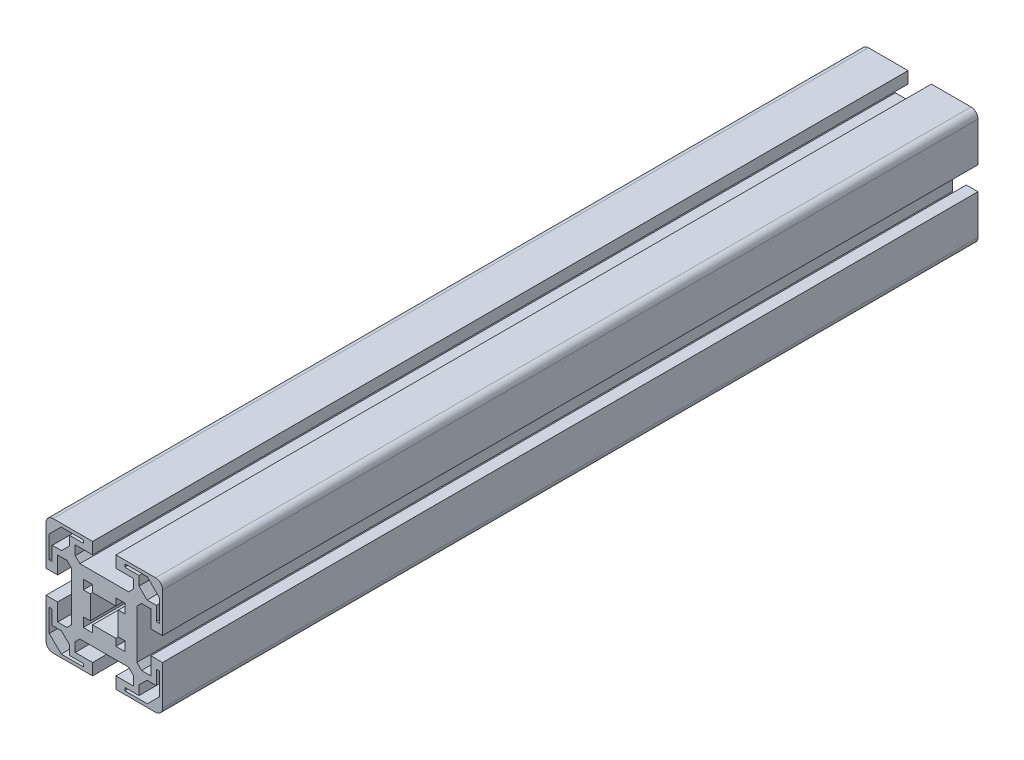
SolidWorks part; units mm, degrees
ref_plane "Alzado" through (0, 0, 0) normal (0, 0, 1) x (1, 0, 0)
ref_plane "Planta" through (0, 0, 0) normal (0, 1, 0) x (1, 0, 0)
ref_plane "Vista lateral" through (0, 0, 0) normal (1, 0, 0) x (0, 0, -1)
sketch "Croquis1" plane through (0, 0, 0) normal (0, 0, 1) x (1, 0, 0)
  line L0 (0, 0) -> (23829.6444, 0) construction
  line L1 (0, 0) -> (0, 23829.6444) construction
  line L2 (5, 25) -> (22, 25)
  line L3 (23.6123, 18.4785) -> (18.4785, 23.6123)
  line L4 (5, 25) -> (5, 20)
  line L5 (5, 20) -> (12.4645, 20)
  line L6 (12.4645, 20) -> (12.4645, 16)
  line L7 (12.4645, 16) -> (10.4645, 14)
  line L8 (10.4645, 14) -> (0, 14)
  line L9 (0, 6) -> (5, 6)
  line L10 (5, 6) -> (5, 9)
  line L11 (5, 9) -> (9, 9)
  line L12 (22.3289, 14.9134) -> (18.3598, 14.9134)
  line L13 (22.3289, 8.8172) -> (22.3289, 14.9134)
  line L14 (23.6123, 8.8172) -> (22.3289, 8.8172)
  line L15 (18.4785, 23.6123) -> (8.8172, 23.6123)
  line L16 (0, 0) -> (38.8156, 38.8156) construction
  line L17 (8.8172, 23.6123) -> (8.8172, 22.3289)
  line L18 (8.8172, 22.3289) -> (14.9134, 22.3289)
  line L19 (14.9134, 22.3289) -> (14.9134, 18.3598)
  line L20 (14.9134, 18.3598) -> (18.3598, 14.9134)
  line L21 (23.6123, 18.4785) -> (23.6123, 8.8172)
  line L22 (9, 5) -> (9, 9)
  line L23 (6, 5) -> (9, 5)
  line L24 (6, 0) -> (6, 5)
  line L25 (14, 10.4645) -> (14, 0)
  line L26 (16, 12.4645) -> (14, 10.4645)
  line L27 (20, 12.4645) -> (16, 12.4645)
  line L28 (20, 5) -> (20, 12.4645)
  line L29 (25, 5) -> (20, 5)
  line L30 (25, 5) -> (25, 22)
  line L31 (0, 14) -> (0, 6)
  line L32 (6, 0) -> (14, 0)
  arc A0 (22, 25) -> (25, 22) centre (22, 22) cw
  point P22 (16.6366, 16.6366)
  point P43 (21.0454, 21.0454)
  dimension "D3" = 3
  dimension "D9" = 12
  dimension "D1" = 5
  dimension "D2" = 50
  dimension "D4" = 10
  dimension "D5" = 6
  dimension "D6" = 45
  dimension "D7" = 5
  dimension "D8" = 4
  dimension "D10" = 6
  dimension "D11" = 5
extrude "Saliente-Extruir1" add sketch "Croquis1" along normal mid plane 350
mirror "Simetría1" about plane through (0, 14, 175) normal (1, 0, 0) of "Saliente-Extruir1"
mirror "Simetría7" about plane through (6, 0, 175) normal (0, 1, 0) of bodies 102
